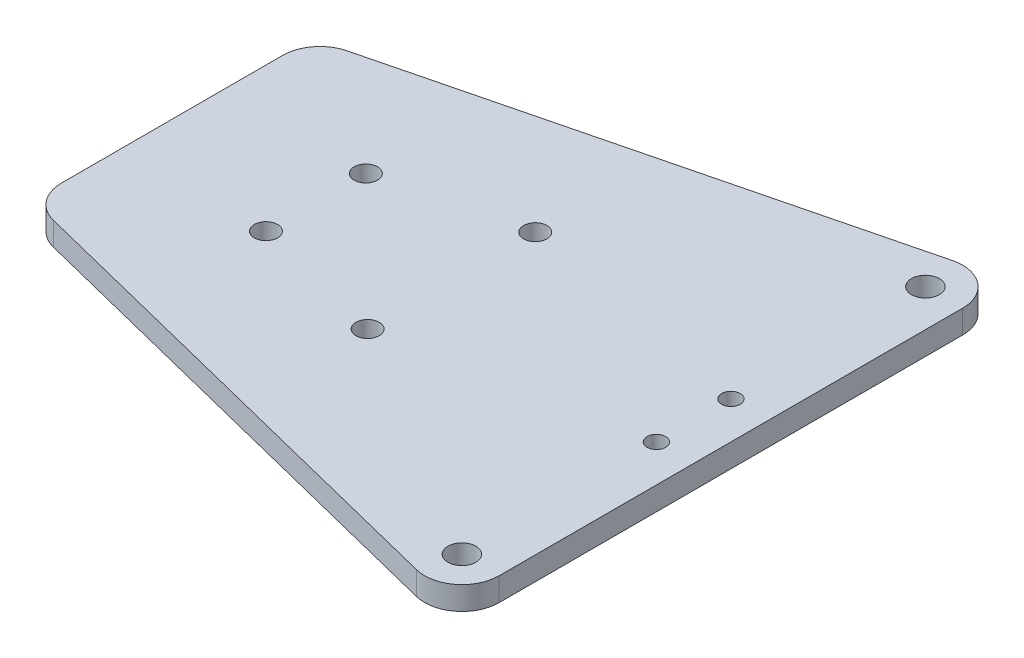
SolidWorks part; units mm, degrees
ref_plane "Front Plane" through (0, 0, 0) normal (0, 0, 1) x (1, 0, 0)
ref_plane "Top Plane" through (0, 0, 0) normal (0, 1, 0) x (1, 0, 0)
ref_plane "Right Plane" through (0, 0, 0) normal (1, 0, 0) x (0, 0, -1)
sketch "Sketch1" plane through (0, 0, 0) normal (0, 1, 0) x (1, 0, 0)
  line L0 (-105.2018, 0) -> (107.0852, 0) construction
  line L1 (-60, -23.7538) -> (-60, 23.7538)
  line L2 (-53.9403, 31.5149) -> (50.0597, 57.5149)
  line L3 (60, 49.7538) -> (60, -49.7538)
  line L4 (-53.9403, -31.5149) -> (50.0597, -57.5149)
  arc A0 (50.0597, 57.5149) -> (60, 49.7538) centre (52, 49.7538) cw
  arc A1 (-60, 23.7538) -> (-53.9403, 31.5149) centre (-52, 23.7538) cw
  arc A2 (50.0597, -57.5149) -> (60, -49.7538) centre (52, -49.7538) ccw
  arc A3 (-60, -23.7538) -> (-53.9403, -31.5149) centre (-52, -23.7538) ccw
  point P9 (60, 60)
  point P12 (-60, 30)
  point P14 (60, 0)
  point P19 (-60, 0)
  dimension "D4" = 8
  dimension "D1" = 30
  dimension "D2" = 60
  dimension "D3" = 60
  dimension "D5" = 60
extrude "Boss-Extrude1" add sketch "Sketch1" along normal mid plane 5
sketch "Sketch2" plane through (0, 2.5, 0) normal (0, 1, 0) x (1, 0, 0)
  line L0 (-74.4204, 0) -> (88.5957, 0) construction
  line L1 (60, -49.7538) -> (60, 49.7538) construction
  line L2 (-29.1043, 10.7239) -> (0, 18) construction
  line L3 (50.0597, 57.5149) -> (-53.9403, 31.5149) construction
  circle A0 centre (52, 49.7538) radius 3
  circle A2 centre (0, 18) radius 2.5
  circle A3 centre (52, -49.7538) radius 3
  circle A4 centre (0, -18) radius 2.5
  circle A6 centre (-29.1043, 10.7239) radius 2.5
  circle A7 centre (-29.1043, -10.7239) radius 2.5
  circle A8 centre (52, 8) radius 2
  circle A9 centre (52, -8) radius 2
  dimension "D1" = 5
  dimension "D2" = 5
  dimension "D3" = 30
  dimension "D6" = 4
  dimension "D4" = 60
  dimension "D5" = 18
  dimension "D7" = 8
  dimension "D8" = 8
extrude "Cut-Extrude1" cut sketch "Sketch2" against normal up to surface (5 mm away) up to face at (-0.8307, -2.5, 0)
